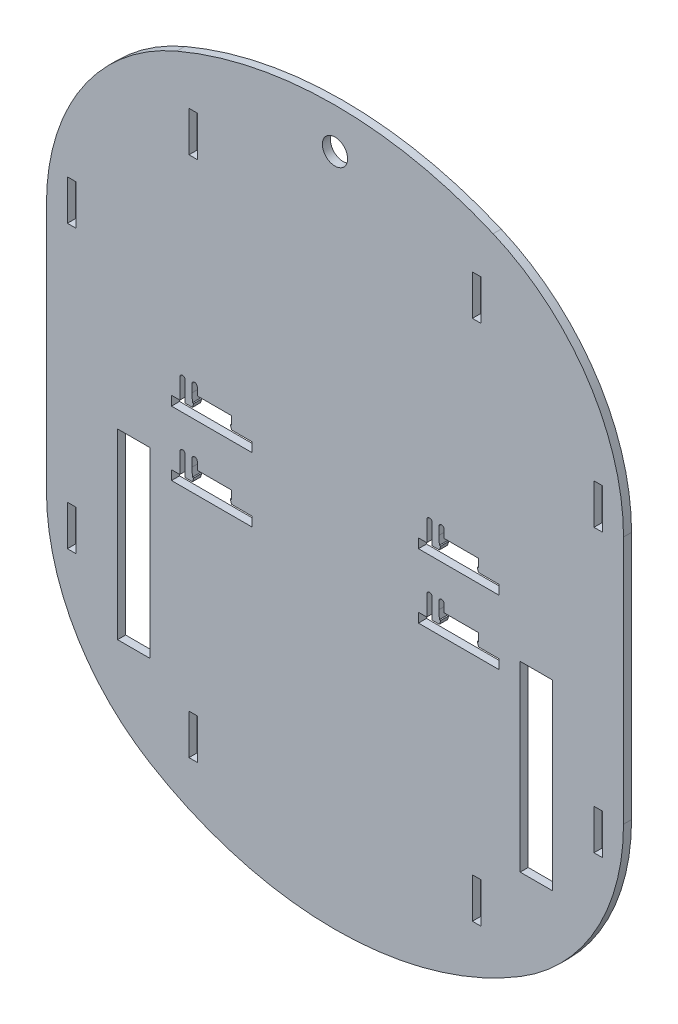
SolidWorks part; units mm, degrees
ref_plane "Front Plane" through (0, 0, 0) normal (0, 0, 1) x (1, 0, 0)
ref_plane "Top Plane" through (0, 0, 0) normal (0, 1, 0) x (1, 0, 0)
ref_plane "Right Plane" through (0, 0, 0) normal (1, 0, 0) x (0, 0, -1)
sketch "Sketch1" plane through (0, 0, 0) normal (0, 0, 1) x (1, 0, 0)
  line L0 (-107.5, -45.3073) -> (-107.5, 47.372) construction
  line L1 (107.5, -45.3073) -> (107.5, 47.372) construction
  line L2 (-107.5, -45.3073) -> (-107.5, 47.372)
  line L3 (107.5, -45.3073) -> (107.5, 47.372)
  arc A0 (-107.5, -45.3073) -> (-69.0094, -113.6956) centre (-27.5, -45.3073) ccw construction
  arc A1 (58.9286, 120.9399) -> (-58.9286, 120.9399) centre (0, -17) ccw construction
  arc A2 (-69.0094, -113.6956) -> (69.0094, -113.6956) centre (0, 0) ccw construction
  arc A3 (69.0094, -113.6956) -> (107.5, -45.3073) centre (27.5, -45.3073) ccw construction
  arc A4 (107.5, 47.372) -> (58.9286, 120.9399) centre (27.5, 47.372) ccw construction
  arc A6 (-58.9286, 120.9399) -> (-107.5, 47.372) centre (-27.5, 47.372) ccw construction
  arc A7 (-107.5, -45.3073) -> (-69.0094, -113.6956) centre (-27.5, -45.3073) ccw
  arc A8 (-69.0094, -113.6956) -> (69.0094, -113.6956) centre (0, 0) ccw
  arc A9 (69.0094, -113.6956) -> (107.5, -45.3073) centre (27.5, -45.3073) ccw
  arc A10 (107.5, 47.372) -> (58.9286, 120.9399) centre (27.5, 47.372) ccw
  arc A11 (58.9286, 120.9399) -> (-58.9286, 120.9399) centre (0, -17) ccw
  arc A12 (-58.9286, 120.9399) -> (-107.5, 47.372) centre (-27.5, 47.372) ccw
extrude "Boss-Extrude1" add sketch "Sketch1" along normal up to vertex (3 mm away)
sketch "Sketch2" plane through (0, 0, 3) normal (0, 0, 1) x (1, 0, 0)
  line L0 (96.5, -80.1785) -> (96.5, 82.2432) construction
  line L1 (99.7, -60) -> (96.5, -60)
  line L8 (99.7, -60) -> (99.7, -45)
  line L9 (99.7, -45) -> (96.5, -45)
  line L10 (96.5, -60) -> (96.5, -45)
  line L11 (130.6075, 0) -> (-151.527, 0) construction
  line L12 (96.5, 60) -> (96.5, 45)
  line L13 (99.7, 45) -> (96.5, 45)
  line L14 (99.7, 60) -> (99.7, 45)
  line L15 (99.7, 60) -> (96.5, 60)
  line L16 (-99.7, 60) -> (-96.5, 60)
  line L17 (0, 0) -> (39.6263, 0) construction
  line L18 (0, 0) -> (0, 30.6591) construction
  line L19 (-99.7, 60) -> (-99.7, 45)
  line L20 (-99.7, 45) -> (-96.5, 45)
  line L21 (-96.5, 60) -> (-96.5, 45)
  line L22 (-96.5, -60) -> (-96.5, -45)
  line L23 (-99.7, -45) -> (-96.5, -45)
  line L24 (-99.7, -60) -> (-99.7, -45)
  line L25 (-99.7, -60) -> (-96.5, -60)
  line L26 (54.19, -107.1612) -> (54.19, -87.2961) construction
  line L27 (54.19, -119.7542) -> (54.19, 119.7542) construction
  line L31 (54.39, 104.7542) -> (54.39, 89.7542)
  line L32 (51.19, -104.7542) -> (54.39, -104.7542)
  line L33 (51.19, -104.7542) -> (51.19, -89.7542)
  line L34 (51.19, -89.7542) -> (54.39, -89.7542)
  line L43 (54.39, -104.7542) -> (54.39, -89.7542)
  line L44 (51.19, 89.7542) -> (54.39, 89.7542)
  line L46 (51.19, 104.7542) -> (51.19, 89.7542)
  line L47 (51.19, 104.7542) -> (54.39, 104.7542)
  line L48 (-51.19, 104.7542) -> (-54.39, 104.7542)
  line L49 (-51.19, 104.7542) -> (-51.19, 89.7542)
  line L50 (-51.19, 89.7542) -> (-54.39, 89.7542)
  line L51 (-54.39, 104.7542) -> (-54.39, 89.7542)
  line L52 (-54.39, -104.7542) -> (-54.39, -89.7542)
  line L53 (-51.19, -89.7542) -> (-54.39, -89.7542)
  line L54 (-51.19, -104.7542) -> (-51.19, -89.7542)
  line L55 (-51.19, -104.7542) -> (-54.39, -104.7542)
  line B0 (31.1, -18.6) -> (61.1, -18.6)
  line B1 (61.1, -18.6) -> (61.1, -15.1)
  line B2 (61.1, -15.1) -> (53.5, -15.1)
  line B3 (53.5, -15.1) -> (53, -13.6)
  line B4 (53, -13.6) -> (53.5, -13.6)
  line B5 (53.5, -13.6) -> (53.5, -10.5)
  line B6 (53.5, -10.5) -> (40.7, -10.5)
  line B7 (40.7, -10.5) -> (40.7, -7.6)
  line B8 (38.7, -7.6) -> (38.7, -10.5)
  line B9 (38.7, -10.5) -> (38.9, -13.6)
  line B10 (38.9, -13.6) -> (39.4, -13.6)
  line B11 (39.4, -13.6) -> (38.9, -15.1)
  line B12 (38.9, -15.1) -> (36.2, -15.1)
  line B13 (36.2, -15.1) -> (36.2, -7.6)
  line B14 (34.2, -7.6) -> (34.2, -15.1)
  line B15 (34.2, -15.1) -> (31.1, -15.1)
  line B16 (31.1, -15.1) -> (31.1, -18.6)
  arc B17 (40.7, -7.6) -> (38.7, -7.6) centre (39.7, -7.6) ccw
  arc B18 (36.2, -7.6) -> (34.2, -7.6) centre (35.2, -7.6) ccw
  line B19 (31.1, 5.4) -> (61.1, 5.4)
  line B20 (61.1, 5.4) -> (61.1, 8.9)
  line B21 (61.1, 8.9) -> (53.5, 8.9)
  line B22 (53.5, 8.9) -> (53, 10.4)
  line B23 (53, 10.4) -> (53.5, 10.4)
  line B24 (53.5, 10.4) -> (53.5, 13.5)
  line B25 (53.5, 13.5) -> (40.7, 13.5)
  line B26 (40.7, 13.5) -> (40.7, 16.4)
  line B27 (38.7, 16.4) -> (38.7, 13.5)
  line B28 (38.7, 13.5) -> (38.9, 10.4)
  line B29 (38.9, 10.4) -> (39.4, 10.4)
  line B30 (39.4, 10.4) -> (38.9, 8.9)
  line B31 (38.9, 8.9) -> (36.2, 8.9)
  line B32 (36.2, 8.9) -> (36.2, 16.4)
  line B33 (34.2, 16.4) -> (34.2, 8.9)
  line B34 (34.2, 8.9) -> (31.1, 8.9)
  line B35 (31.1, 8.9) -> (31.1, 5.4)
  arc B36 (40.7, 16.4) -> (38.7, 16.4) centre (39.7, 16.4) ccw
  arc B37 (36.2, 16.4) -> (34.2, 16.4) centre (35.2, 16.4) ccw
  line B38 (-60.9, -18.6) -> (-30.9, -18.6)
  line B39 (-30.9, -18.6) -> (-30.9, -15.1)
  line B40 (-30.9, -15.1) -> (-38.5, -15.1)
  line B41 (-38.5, -15.1) -> (-39, -13.6)
  line B42 (-39, -13.6) -> (-38.5, -13.6)
  line B43 (-38.5, -13.6) -> (-38.5, -10.5)
  line B44 (-38.5, -10.5) -> (-51.3, -10.5)
  line B45 (-51.3, -10.5) -> (-51.3, -7.6)
  line B46 (-53.3, -7.6) -> (-53.3, -10.5)
  line B47 (-53.3, -10.5) -> (-53.1, -13.6)
  line B48 (-53.1, -13.6) -> (-52.6, -13.6)
  line B49 (-52.6, -13.6) -> (-53.1, -15.1)
  line B50 (-53.1, -15.1) -> (-55.8, -15.1)
  line B51 (-55.8, -15.1) -> (-55.8, -7.6)
  line B52 (-57.8, -7.6) -> (-57.8, -15.1)
  line B53 (-57.8, -15.1) -> (-60.9, -15.1)
  line B54 (-60.9, -15.1) -> (-60.9, -18.6)
  arc B55 (-51.3, -7.6) -> (-53.3, -7.6) centre (-52.3, -7.6) ccw
  arc B56 (-55.8, -7.6) -> (-57.8, -7.6) centre (-56.8, -7.6) ccw
  line B57 (-60.9, 5.4) -> (-30.9, 5.4)
  line B58 (-30.9, 5.4) -> (-30.9, 8.9)
  line B59 (-30.9, 8.9) -> (-38.5, 8.9)
  line B60 (-38.5, 8.9) -> (-39, 10.4)
  line B61 (-39, 10.4) -> (-38.5, 10.4)
  line B62 (-38.5, 10.4) -> (-38.5, 13.5)
  line B63 (-38.5, 13.5) -> (-51.3, 13.5)
  line B64 (-51.3, 13.5) -> (-51.3, 16.4)
  line B65 (-53.3, 16.4) -> (-53.3, 13.5)
  line B66 (-53.3, 13.5) -> (-53.1, 10.4)
  line B67 (-53.1, 10.4) -> (-52.6, 10.4)
  line B68 (-52.6, 10.4) -> (-53.1, 8.9)
  line B69 (-53.1, 8.9) -> (-55.8, 8.9)
  line B70 (-55.8, 8.9) -> (-55.8, 16.4)
  line B71 (-57.8, 16.4) -> (-57.8, 8.9)
  line B72 (-57.8, 8.9) -> (-60.9, 8.9)
  line B73 (-60.9, 8.9) -> (-60.9, 5.4)
  arc B74 (-51.3, 16.4) -> (-53.3, 16.4) centre (-52.3, 16.4) ccw
  arc B75 (-55.8, 16.4) -> (-57.8, 16.4) centre (-56.8, 16.4) ccw
  dimension "D1" = 15
  dimension "D2" = 15
  dimension "D3" = 45
  dimension "D4" = 0.2
sketch_block_instance "T-slot-1"
sketch_block "T-slot" parameters "D2"=1, "D18"=1, "D1"=5, "D3"=0.5, "D4"=14.8, "D5"=0.2, "D6"=3.1, "D7"=1.5, "D8"=30, "D9"=3.5, "D10"=5, "D11"=6, "D12"=2.5, "D13"=5, "D14"=6, "D15"=7.3, "D16"=0.2, "D17"=1.5, "D19"=15, "D20"=2, "D21"=2.9
sketch_block_instance "T-slot-3"
sketch_block_instance "T-slot-4"
sketch_block_instance "T-slot-5"
extrude "mounting slots" cut sketch "Sketch2" against normal up to next
sketch "Sketch3" plane through (0, 0, 3) normal (0, 0, 1) x (1, 0, 0)
  line L0 (0, -154.1611) -> (0, 154.1611) construction
  line L1 (0, 0) -> (0, -85.579) construction
  line L2 (69, -80) -> (81, -80)
  line L3 (69, -80) -> (69, -12)
  line L4 (69, -12) -> (81, -12)
  line L5 (81, -80) -> (81, -12)
  line L6 (-69, -80) -> (-81, -80)
  line L7 (-69, -80) -> (-69, -12)
  line L8 (-69, -12) -> (-81, -12)
  line L9 (-81, -80) -> (-81, -12)
  line L10 (75, -91.4663) -> (75, 1.4663) construction
  line L11 (75, -45) -> (-75, -45) construction
  circle A0 centre (0, 118) radius 4.7
  arc A1 (58.9286, 120.9399) -> (-58.9286, 120.9399) centre (0, -17) ccw construction
  dimension "D1" = 9.4
  dimension "D2" = 15
  dimension "D3" = 12
  dimension "D4" = 35
  dimension "D5" = 33
extrude "caster and wheel slots" cut sketch "Sketch3" against normal up to next
